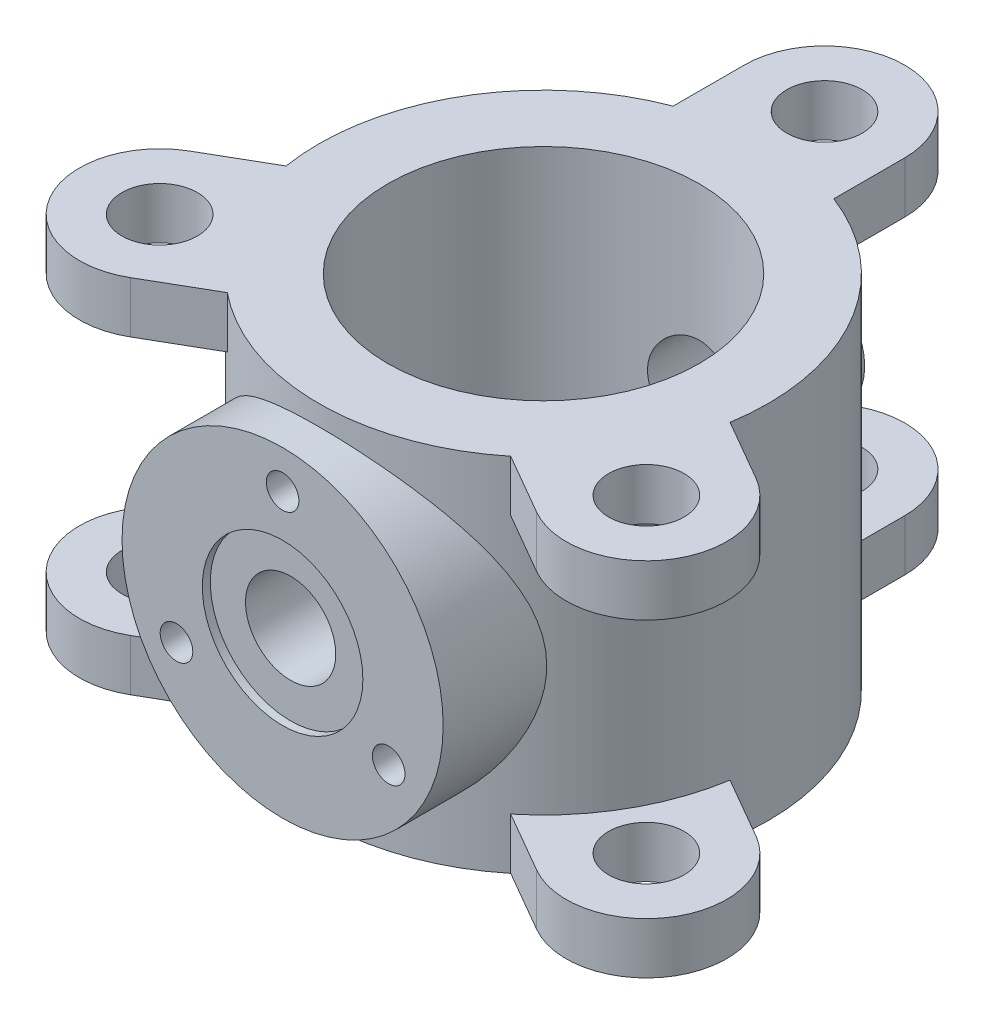
SolidWorks part; units mm, degrees
ref_plane "Front Plane" through (0, 0, 0) normal (0, 0, 1) x (1, 0, 0)
ref_plane "Top Plane" through (0, 0, 0) normal (0, 1, 0) x (1, 0, 0)
ref_plane "Right Plane" through (0, 0, 0) normal (1, 0, 0) x (0, 0, -1)
sketch "Sketch1" plane through (0, 0, 0) normal (0, 1, 0) x (1, 0, 0)
  circle A0 centre (0, 0) radius 140
  circle A1 centre (0, 0) radius 97
  dimension "D1" = 280
  dimension "D2" = 194
extrude "Boss-Extrude1" add sketch "Sketch1" along normal mid plane 225
ref_plane "Plane1" through (0, 0, 162.5) normal (0, 0, 1) x (1, 0, 0)
sketch "Sketch2" plane through (0, 0, 162.5) normal (0, 0, 1) x (1, 0, 0)
  circle A0 centre (0, 0) radius 100
  dimension "D1" = 200
extrude "Boss-Extrude2" add sketch "Sketch2" against normal up to next
ref_plane "Plane2" through (0, 0, -162.5) normal (0, 0, 1) x (1, 0, 0)
sketch "Sketch3" plane through (0, 0, -162.5) normal (0, 0, 1) x (1, 0, 0)
  circle A0 centre (0, 0) radius 37.5
  dimension "D1" = 75
extrude "Boss-Extrude3" add sketch "Sketch3" along normal up to next
hole_wizard "Hole1" positions "Sketch4" profile "Sketch5" legacy
sketch "Sketch4" plane through (0, 0, 162.5) normal (0, 0, 1) x (1, 0, 0)
  point P0 (0, 76.3)
  dimension "D1" = 76.3
sketch "Sketch5" plane through (0, 76.3, 162.5) normal (1, 0, 0) x (0, -1, 0)
  line L0 (0, 0) -> (0, 30)
  line L1 (0, 30) -> (10.15, 30)
  line L2 (10.15, 30) -> (10.15, 0)
  line L3 (10.15, 0) -> (0, 0)
  line L4 (0, 110) -> (0, -10) construction
  dimension "Diameter" = 20.3
  dimension "Depth" = 30
pattern_circular "CirPattern1" count 3 over 360 about axis through (0, 0, 0) along (0, 0, 1) of "Hole1"
hole_wizard "Hole2" positions "Sketch6" profile "Sketch7" legacy end condition through all
sketch "Sketch6" plane through (0, 0, 162.5) normal (0, 0, 1) x (1, 0, 0)
  point P0 (0, 0)
sketch "Sketch7" plane through (0, 0, 162.5) normal (1, 0, 0) x (0, -1, 0)
  line L0 (0, 0) -> (0, 325)
  line L1 (0, 325) -> (28.1, 325)
  line L2 (28.1, 325) -> (28.1, 5)
  line L3 (28.1, 5) -> (50, 5)
  line L4 (50, 5) -> (50, 0)
  line L5 (50, 0) -> (0, 0)
  line L6 (0, 110) -> (0, -10) construction
  dimension "Diameter" = 56.2
  dimension "Depth" = 325
  dimension "C-Bore Diameter" = 100
  dimension "C-Bore Depth" = 5
sketch "Sketch8" plane through (0, 112.5, 0) normal (0, 1, 0) x (1, 0, 0)
  line L0 (-50, 175) -> (-50, 130.767)
  line L1 (50, 175) -> (50, 130.767)
  arc A0 (50, 175) -> (-50, 175) centre (0, 175) ccw
  circle A1 centre (0, 0) radius 140 construction
  arc A2 (50, 130.767) -> (-50, 130.767) centre (0, 0) ccw
  dimension "D1" = 100
  dimension "D2" = 175
extrude "Boss-Extrude4" add sketch "Sketch8" against normal blind 32
pattern_circular "CirPattern2" count 3 over 360 about axis through (0, 0, 0) along (0, 1, 0) of "Boss-Extrude4"
hole_wizard "Hole3" positions "Sketch9" profile "Sketch10" legacy
sketch "Sketch9" plane through (0, 112.5, 0) normal (0, 1, 0) x (1, 0, 0)
  point P0 (0, 175)
  point P3 (151.5544, -87.5)
  point P6 (-151.5544, -87.5)
  point P10 (0, 0)
sketch "Sketch10" plane through (0, 112.5, -175) normal (1, 0, 0) x (0, 0, 1)
  line L0 (0, 0) -> (0, 225)
  line L1 (0, 225) -> (23.5, 225)
  line L2 (23.5, 225) -> (23.5, 0)
  line L3 (23.5, 0) -> (0, 0)
  line L4 (0, 110) -> (0, -10) construction
  dimension "Diameter" = 47
  dimension "Depth" = 225
mirror "Mirror1" about plane through (0, 0, 0) normal (0, 1, 0) of "CirPattern2", "Boss-Extrude4", "Hole3"
